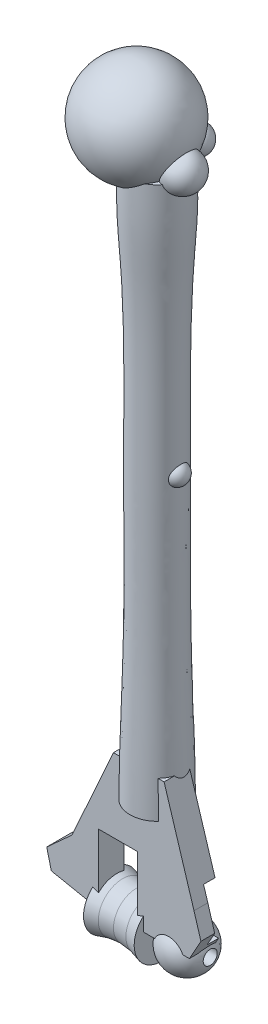
SolidWorks part; units mm, degrees
material "Nylon 101"
ref_plane "Alzado" through (0, 0, 0) normal (0, 0, 1) x (1, 0, 0)
ref_plane "Planta" through (0, 0, 0) normal (0, 1, 0) x (1, 0, 0)
ref_plane "Vista lateral" through (0, 0, 0) normal (1, 0, 0) x (0, 0, -1)
sketch "Sketch1" plane through (0, 0, 0) normal (0, 0, 1) x (1, 0, 0)
  line L0 (20.8, -252) -> (9, -252)
  line L1 (9, -252) -> (9, -12)
  line L2 (9, -12) -> (21.5, -12)
  line L3 (9, -256) -> (9, -8) construction
  spline S0 degree 3 poles (21.5, -12) (21.5427, -18.0023) (21.6375, -31.3516) (18.8503, -67.2853) (19.6256, -124.0104) (18.8611, -186.013) (20.5373, -229.996) (20.7443, -247.3332) (20.8, -252) knots 0 0 0 0 0.074984 0.166767 0.450061 0.783321 0.941674 1 1 1 1
revolve "Diafisis" add sketch "Sketch1" angle 360 about L3
sketch "Sketch2" plane through (0, 0, 0) normal (0, 0, 1) x (1, 0, 0)
  line L0 (0, -22) -> (0, 22)
  line L1 (0, -26) -> (0, 26) construction
  arc A0 (0, 22) -> (0, -22) centre (0, 0) cw
revolve "Cabeza_humeral" add sketch "Sketch2" angle 360 about L1
sketch "Sketch3" plane through (0, 0, 0) normal (0, 0, 1) x (1, 0, 0)
  line L0 (20, -18) -> (20, -2)
  line L1 (20, -22) -> (20, 2) construction
  arc A0 (20, -2) -> (20, -18) centre (20, -10) cw
revolve "Tuberculo_mayor" add sketch "Sketch3" angle 360 about L1
ref_plane "Plane2" through (0, 0, -17) normal (0, 0, 1) x (1, 0, 0)
sketch "Sketch4" plane through (0, 0, -17) normal (0, 0, 1) x (1, 0, 0)
  line L0 (9, -18) -> (9, -6)
  line L1 (9, -22) -> (9, -2) construction
  arc A0 (9, -6) -> (9, -18) centre (9, -12) cw
revolve "Tuberculo_menor" add sketch "Sketch4" angle 360 about L1
sketch "Sketch5" plane through (0, 0, 0) normal (0, 0, 1) x (1, 0, 0)
  line L0 (17.5, -129.5) -> (17.5, -120.5)
  line L1 (17.5, -133.5) -> (17.5, -116.5) construction
  arc A0 (17.5, -120.5) -> (17.5, -129.5) centre (17.5, -125) cw
revolve "Tuberosidad_deltoidea" add sketch "Sketch5" angle 360 about L1
ref_plane "Plane4" through (0, 0, -3) normal (0, 0, 1) x (1, 0, 0)
sketch "Sketch6" plane through (0, 0, -3) normal (0, 0, 1) x (1, 0, 0)
  line L0 (-2, -236) -> (20, -236)
  line L1 (20, -236) -> (33, -278)
  line L2 (33, -278) -> (36, -288)
  line L3 (36, -288) -> (31, -297)
  line L4 (31, -297) -> (-14, -297)
  line L5 (-14, -297) -> (-29, -294)
  line L6 (-29, -294) -> (-31, -286)
  line L7 (-31, -286) -> (-20, -276)
  line L8 (-20, -276) -> (-2, -236)
extrude "Paleta_distal" add sketch "Sketch6" along normal blind 11
ref_plane "Plane6" through (0, 0, -4) normal (0, 0, 1) x (1, 0, 0)
sketch "Sketch7" plane through (0, 0, -4) normal (0, 0, 1) x (1, 0, 0)
  line L0 (-8.5, -300) -> (8.5, -300)
  line L1 (8.5, -300) -> (8.5, -268)
  line L2 (8.5, -268) -> (-8.5, -268)
  line L3 (-8.5, -268) -> (-8.5, -300)
extrude "Fosa_olecraneana" cut sketch "Sketch7" along normal blind 13
sketch "Sketch8" plane through (0, 0, -4) normal (0, 0, 1) x (1, 0, 0)
  line L0 (9.5, -294) -> (36.5, -294)
  line L1 (36.5, -294) -> (36.5, -272)
  line L2 (36.5, -272) -> (9.5, -272)
  line L3 (9.5, -272) -> (9.5, -294)
extrude "Fosa_radial" cut sketch "Sketch8" along normal blind 6
sketch "Sketch9" plane through (0, 0, 0) normal (0, 0, 1) x (1, 0, 0)
  line L0 (-11, -300) -> (-11, -288)
  line L1 (-11, -288) -> (-6, -289.4)
  line L2 (-6, -289.4) -> (0, -290)
  line L3 (0, -290) -> (6, -289.4)
  line L4 (6, -289.4) -> (11, -288)
  line L5 (11, -288) -> (11, -300)
  line L6 (11, -300) -> (-11, -300)
  line L7 (-15, -300) -> (15, -300) construction
revolve "Troclea" add sketch "Sketch9" angle 360 about L7
sketch "Sketch10" plane through (0, 0, 0) normal (0, 0, 1) x (1, 0, 0)
  line L0 (22, -310.5) -> (22, -289.5)
  line L1 (22, -314.5) -> (22, -285.5) construction
  arc A0 (22, -289.5) -> (22, -310.5) centre (22, -300) cw
revolve "Capitulo" add sketch "Sketch10" angle 360 about L1
sketch "Sketch11" plane through (0, 0, 0) normal (1, 0, 0) x (0, 0, -1)
  circle A0 centre (0, -300) radius 3.05
extrude "Agujero_eje_codo" cut sketch "Sketch11" against normal mid plane 2000
